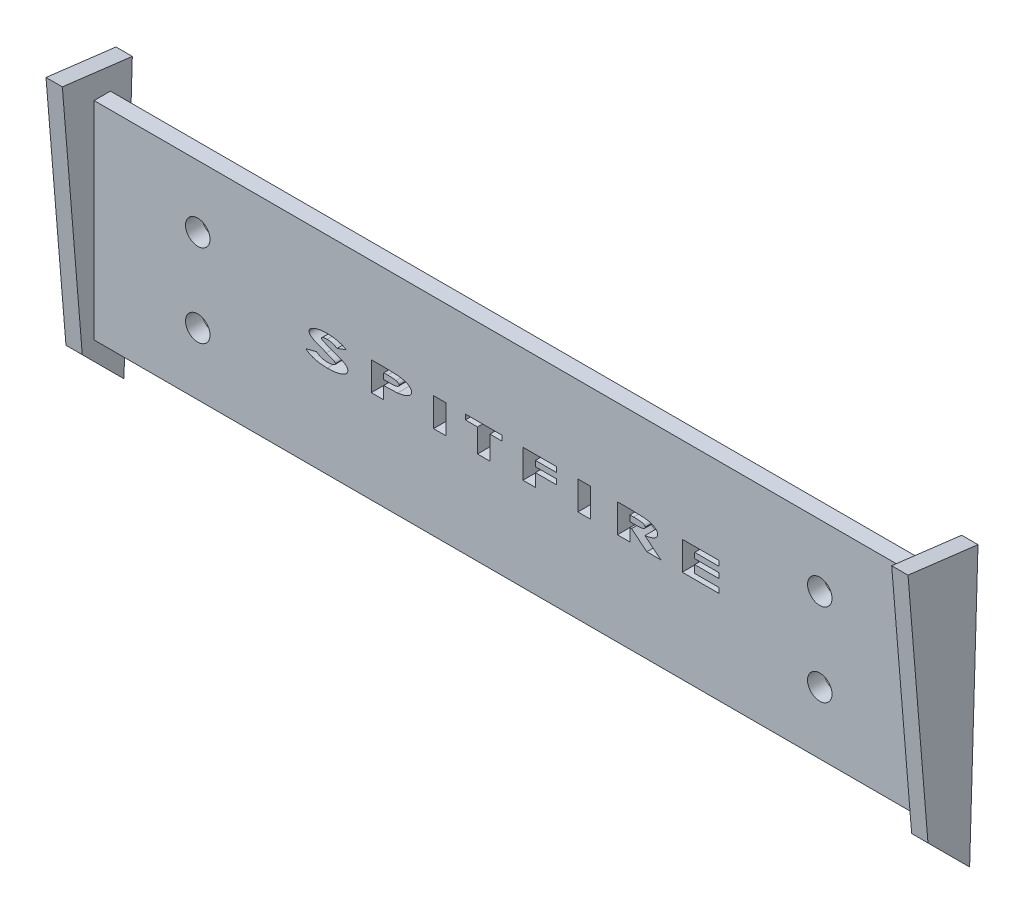
SolidWorks part; units mm, degrees
ref_plane "Front Plane" through (0, 0, 0) normal (0, 0, 1) x (1, 0, 0)
ref_plane "Top Plane" through (0, 0, 0) normal (0, 1, 0) x (1, 0, 0)
ref_plane "Right Plane" through (0, 0, 0) normal (1, 0, 0) x (0, 0, -1)
sketch "Sketch1" plane through (0, 0, 0) normal (0, 0, 1) x (1, 0, 0)
  line L1 (50.8, -12.7) -> (-50.8, -12.7)
  line L2 (50.8, -12.7) -> (50.8, 12.7)
  line L3 (50.8, 12.7) -> (-50.8, 12.7)
  line L4 (-50.8, -12.7) -> (-50.8, 12.7)
  line L5 (50.8, -12.7) -> (-50.8, 12.7) construction
  line L6 (50.8, 12.7) -> (-50.8, -12.7) construction
  point P0 (0, 0)
  dimension "D1" = 101.6
  dimension "D2" = 25.4
extrude "Boss-Extrude1" add sketch "Sketch1" along normal blind 2
sketch "Sketch2" plane through (-50.8, 0, 0) normal (-1, 0, 0) x (0, 0, 1)
  line L0 (5.8918, 16.0955) -> (-2.682, 15.0435)
  line L1 (-2.682, 15.0435) -> (-1.6563, -18.6466)
  line L2 (-1.6563, -18.6466) -> (3.4459, -13.5444)
  line L3 (3.4459, -13.5444) -> (5.8918, 16.0955)
extrude "Boss-Extrude2" add sketch "Sketch2" along normal blind 2
sketch "Sketch3" plane through (50.8, 0, 0) normal (1, 0, 0) x (0, 0, -1)
  line L0 (1.6563, -18.6466) -> (2.682, 15.0435)
  line L1 (2.682, 15.0435) -> (-5.8918, 16.0955)
  line L2 (-5.8918, 16.0955) -> (-3.4459, -13.5444)
  line L3 (-3.4459, -13.5444) -> (1.6563, -18.6466)
extrude "Boss-Extrude3" add sketch "Sketch3" along normal blind 2
sketch "Sketch7" plane through (0, 0, 2) normal (0, 0, 1) x (1, 0, 0)
  line L0 (-50.8, 0) -> (50.8, 0) construction
  line L1 (-50.8, 12.7) -> (-50.8, -12.7) construction
  line L2 (50.8, -12.7) -> (50.8, 12.7) construction
  line L3 (-50.8, -5.08) -> (50.8, -5.08) construction
  line L4 (-50.8, -13.5444) -> (-50.8, 16.0955) construction
  line L5 (-50.8, 5.08) -> (50.8, 5.08) construction
  line L6 (50.8, 16.0955) -> (50.8, -13.5444) construction
  line L7 (0, 5.08) -> (0, -5.08) construction
  line L8 (-38.1, 5.08) -> (-38.1, -5.08) construction
  line L9 (38.1, 5.08) -> (38.1, -5.08) construction
  circle A0 centre (-38.1, 5.08) radius 1.5
  circle A1 centre (-38.1, -5.08) radius 1.5
  circle A2 centre (38.1, -5.08) radius 1.5
  circle A3 centre (38.1, 5.08) radius 1.5
  dimension "D5" = 3
  dimension "D1" = 5.08
  dimension "D2" = 5.08
  dimension "D3" = 38.1
  dimension "D4" = 38.1
extrude "Cut-Extrude1" cut sketch "Sketch7" against normal blind 2.54
sketch "Sketch8" plane through (0, 0, 2) normal (0, 0, 1) x (1, 0, 0)
  text T0 "<b>SPITFIRE</b>" font "Century Gothic" height 3.5
extrude "Cut-Extrude2" cut sketch "Sketch8" against normal blind 2.54
